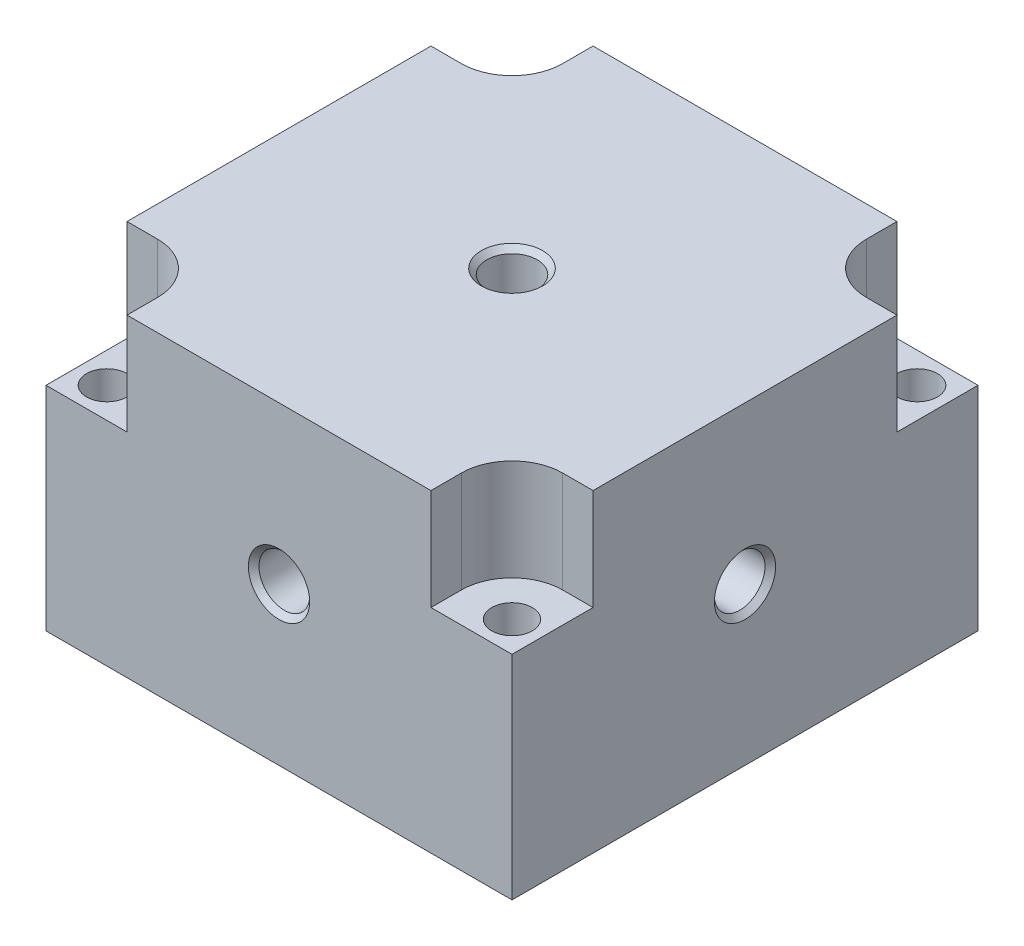
SolidWorks part; units mm, degrees
material "1060 合金"
ref_plane "前视基准面" through (0, 0, 0) normal (0, 0, 1) x (1, 0, 0)
ref_plane "上视基准面" through (0, 0, 0) normal (0, 1, 0) x (1, 0, 0)
ref_plane "右视基准面" through (0, 0, 0) normal (1, 0, 0) x (0, 0, -1)
other "Configuration Table"
sketch "草图1" plane through (0, 0, 0) normal (0, 1, 0) x (1, 0, 0)
  line L1 (-23, 23) -> (23, 23)
  line L2 (-23, 23) -> (-23, -23)
  line L3 (-23, -23) -> (23, -23)
  line L4 (23, 23) -> (23, -23)
  line L5 (-23, 23) -> (23, -23) construction
  line L6 (-23, -23) -> (23, 23) construction
  point P0 (0, 0)
  dimension "D1" = 46
  dimension "D2" = 46
extrude "凸台-拉伸1" add sketch "草图1" along normal mid plane 31
sketch "草图2" plane through (0, 15.5, 0) normal (0, 1, 0) x (1, 0, 0)
  line L16 (15, 20) -> (15, 23)
  line L17 (-20, 20) -> (20, 20) construction
  line L18 (-20, 20) -> (-20, -20) construction
  line L19 (-20, -20) -> (20, -20) construction
  line L20 (20, 20) -> (20, -20) construction
  line L21 (-20, 20) -> (20, -20) construction
  line L22 (-20, -20) -> (20, 20) construction
  line L23 (23, 23) -> (-23, 23) construction
  line L24 (15, 23) -> (23, 23)
  line L25 (20, 15) -> (23, 15)
  line L26 (23, -23) -> (23, 23) construction
  line L27 (23, 15) -> (23, 23)
  line L28 (20, -15) -> (23, -15)
  line L29 (23, -15) -> (23, -23)
  line L30 (15, -23) -> (23, -23)
  line L31 (15, -20) -> (15, -23)
  line L32 (-15, -20) -> (-15, -23)
  line L33 (-15, -23) -> (-23, -23)
  line L34 (-23, -15) -> (-23, -23)
  line L35 (-20, -15) -> (-23, -15)
  line L36 (-20, 15) -> (-23, 15)
  line L37 (-23, 15) -> (-23, 23)
  line L38 (-15, 23) -> (-23, 23)
  line L39 (-15, 20) -> (-15, 23)
  arc A0 (15, 20) -> (20, 15) centre (20, 20) ccw
  arc A1 (20, -15) -> (15, -20) centre (20, -20) ccw
  arc A2 (-15, -20) -> (-20, -15) centre (-20, -20) ccw
  arc A3 (-20, 15) -> (-15, 20) centre (-20, 20) ccw
  point P0 (0, 0)
  point P38 (0, 0)
  dimension "D3" = 10
  dimension "D1" = 40
  dimension "D2" = 40
  dimension "D4" = 4
extrude "切除-拉伸1" cut sketch "草图2" against normal blind 10
sketch "草图4" plane through (0, 5.5, 0) normal (0, 1, 0) x (1, 0, 0)
  circle A0 centre (20, 20) radius 2
  arc A1 (15, 20) -> (20, 15) centre (20, 20) ccw construction
  circle A2 centre (20, -20) radius 2
  circle A3 centre (-20, -20) radius 2
  circle A4 centre (-20, 20) radius 2
  point P14 (0, 0)
  dimension "D1" = 4
  dimension "D2" = 4
extrude "切除-拉伸2" cut sketch "草图4" against normal through all
hole_wizard "M6 螺纹孔1" positions "草图5" profile "草图6" tap size "M6" standard "GB"
sketch "草图5" plane through (0, 0, 23) normal (0, 0, 1) x (1, 0, 0)
  point P0 (0, 0)
sketch "草图6" plane through (0, 0, 23) normal (1, 0, 0) x (0, -1, 0)
  line L0 (0, 0) -> (0, 8.5022)
  line L1 (0, 8.5022) -> (2.5, 7)
  line L2 (2.5, 7) -> (2.5, 0.525)
  line L3 (2.5, 0.525) -> (3.025, 0)
  line L5 (3.025, 0) -> (0, 0)
  line L6 (-2.5, 0.525) -> (-3.025, 0) construction
  line L10 (0, 8.5022) -> (-2.5, 7) construction
  line L11 (0, -6.35) -> (0, 107.95) construction
  dimension "螺纹孔钻头直径" = 5
  dimension "螺纹孔钻头深度" = 7
  dimension "近端锥形沉头孔直径" = 6.05
  dimension "近端锥形沉头孔角度" = 90
  dimension "导头角度" = 118
cosmetic thread "孔螺蚊线1" parameters "D1"=4, "D2"=6
pattern_circular "阵列(圆周)1" count 4 over 360 about axis through (0, 15.5, 0) along (0, 1, 0) of "M6 螺纹孔1"
hole_wizard "M6 螺纹孔2" positions "草图7" profile "草图8" tap size "M6" standard "GB"
sketch "草图7" plane through (0, 15.5, 0) normal (0, 1, 0) x (1, 0, 0)
  point P0 (0, 0)
sketch "草图8" plane through (0, 15.5, 0) normal (1, 0, 0) x (0, 0, 1)
  line L0 (0, 0) -> (0, 8.5022)
  line L1 (0, 8.5022) -> (2.5, 7)
  line L2 (2.5, 7) -> (2.5, 0.525)
  line L3 (2.5, 0.525) -> (3.025, 0)
  line L5 (3.025, 0) -> (0, 0)
  line L6 (-2.5, 0.525) -> (-3.025, 0) construction
  line L10 (0, 8.5022) -> (-2.5, 7) construction
  line L11 (0, -6.35) -> (0, 107.95) construction
  dimension "螺纹孔钻头直径" = 5
  dimension "螺纹孔钻头深度" = 7
  dimension "近端锥形沉头孔直径" = 6.05
  dimension "近端锥形沉头孔角度" = 90
  dimension "导头角度" = 118
cosmetic thread "孔螺蚊线2" parameters "D1"=4, "D2"=6
sketch "草图9" plane through (0, 0, 23) normal (0, 0, 1) x (1, 0, 0)
  circle A0 centre (0, 0) radius 15
  dimension "D1" = 30
